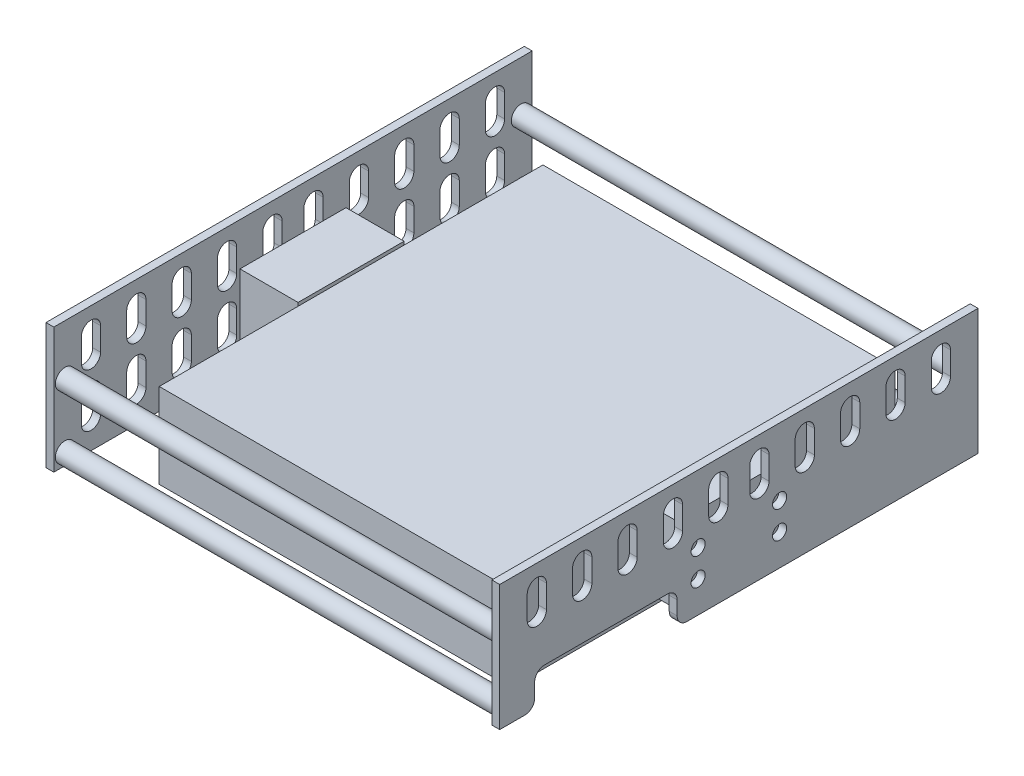
SolidWorks part; units mm, degrees
ref_plane "Front Plane" through (0, 0, 0) normal (0, 0, 1) x (1, 0, 0)
ref_plane "Top Plane" through (0, 0, 0) normal (0, 1, 0) x (1, 0, 0)
ref_plane "Right Plane" through (0, 0, 0) normal (1, 0, 0) x (0, 0, -1)
sketch "Sketch1" plane through (0, 0, 0) normal (1, 0, 0) x (0, 0, -1)
  line L0 (0, 0) -> (0, -16.4338) construction
  line L1 (0, 0) -> (55.8004, 0) construction
  line L2 (0, -16.4338) -> (117.9322, -16.4338) construction
  line L3 (117.9322, -16.4338) -> (117.9322, 0) construction
  line L4 (-2.5019, -18.9357) -> (120.4341, -18.9357) construction
  line L5 (-2.5019, 2.5019) -> (120.4341, 2.5019) construction
  line L6 (-2.5019, 2.5019) -> (-2.5019, -18.9357) construction
  line L7 (120.4341, 2.5019) -> (120.4341, -18.9357) construction
  circle A0 centre (0, 0) radius 2.5019
  circle A1 centre (0, -16.4338) radius 2.5019
  circle A2 centre (117.9322, -16.4338) radius 2.5019
  circle A3 centre (117.9322, 0) radius 2.5019
  dimension "D2" = 5.0038
  dimension "D3" = 21.4376
  dimension "D4" = 122.936
extrude "Boss-Extrude1" add sketch "Sketch1" along normal blind 115.316
ref_plane "Plane1" through (12.7, 0, 0) normal (1, 0, 0) x (0, 0, -1)
sketch "Sketch5" plane through (0, 0, 0) normal (1, 0, 0) x (0, 0, -1)
  line L4 (0, 0) -> (117.9322, -16.4338) construction
  line L5 (58.9661, 12.954) -> (58.9661, -19.558) construction
  line L6 (4.2291, -14.9987) -> (4.2291, 9.7028) construction
  line L8 (6.7183, 1.27) -> (6.7183, 7.2136) construction
  line L10 (4.2291, 9.7028) -> (113.7031, 9.7028) construction
  line L15 (113.7031, -14.9987) -> (4.2291, -14.9987) construction
  line L20 (117.9322, 0) -> (0, -16.4338) construction
  line L29 (64.2747, 1.27) -> (64.2747, 7.2136) construction
  line L38 (66.7639, 1.27) -> (66.7639, 7.2136)
  line L45 (61.7855, 1.27) -> (61.7855, 7.2136)
  line L52 (64.2747, -12.5095) -> (64.2747, -6.5659) construction
  line L61 (66.7639, -12.5095) -> (66.7639, -6.5659)
  line L70 (61.7855, -12.5095) -> (61.7855, -6.5659)
  line L76 (-2.8829, -19.558) -> (120.8151, -19.558)
  line L77 (-2.8829, -19.558) -> (-2.8829, 12.954)
  line L78 (-2.8829, 12.954) -> (120.8151, 12.954)
  line L79 (120.8151, -19.558) -> (120.8151, 12.954)
  line L80 (76.0095, -12.5095) -> (76.0095, -6.5659) construction
  line L81 (78.4987, -12.5095) -> (78.4987, -6.5659)
  line L82 (4.2291, 1.27) -> (4.2291, 7.2136)
  line L83 (9.2075, 1.27) -> (9.2075, 7.2136)
  line L84 (4.2291, 9.7028) -> (9.2075, 9.7028) construction
  line L85 (9.2075, 9.7028) -> (9.2075, -1.2192) construction
  line L86 (9.2075, -1.2192) -> (4.2291, -1.2192) construction
  line L87 (4.2291, -1.2192) -> (4.2291, 9.7028) construction
  line L88 (18.4531, 1.27) -> (18.4531, 7.2136) construction
  line L89 (15.9639, 1.27) -> (15.9639, 7.2136)
  line L90 (20.9423, 1.27) -> (20.9423, 7.2136)
  line L91 (30.1879, 1.27) -> (30.1879, 7.2136) construction
  line L92 (27.6987, 1.27) -> (27.6987, 7.2136)
  line L93 (32.6771, 1.27) -> (32.6771, 7.2136)
  line L94 (41.9227, 1.27) -> (41.9227, 7.2136) construction
  line L95 (39.4335, 1.27) -> (39.4335, 7.2136)
  line L96 (44.4119, 1.27) -> (44.4119, 7.2136)
  line L97 (53.6575, 1.27) -> (53.6575, 7.2136) construction
  line L98 (51.1683, 1.27) -> (51.1683, 7.2136)
  line L99 (56.1467, 1.27) -> (56.1467, 7.2136)
  line L100 (18.4531, -12.5095) -> (18.4531, -6.5659) construction
  line L101 (15.9639, -12.5095) -> (15.9639, -6.5659)
  line L102 (20.9423, -12.5095) -> (20.9423, -6.5659)
  line L103 (30.1879, -12.5095) -> (30.1879, -6.5659) construction
  line L104 (27.6987, -12.5095) -> (27.6987, -6.5659)
  line L105 (32.6771, -12.5095) -> (32.6771, -6.5659)
  line L106 (41.9227, -12.5095) -> (41.9227, -6.5659) construction
  line L107 (39.4335, -12.5095) -> (39.4335, -6.5659)
  line L108 (44.4119, -12.5095) -> (44.4119, -6.5659)
  line L109 (53.6575, -12.5095) -> (53.6575, -6.5659) construction
  line L110 (51.1683, -12.5095) -> (51.1683, -6.5659)
  line L111 (56.1467, -12.5095) -> (56.1467, -6.5659)
  line L112 (6.7183, -12.5095) -> (6.7183, -6.5659) construction
  line L113 (4.2291, -12.5095) -> (4.2291, -6.5659)
  line L114 (9.2075, -12.5095) -> (9.2075, -6.5659)
  line L116 (73.5203, -12.5095) -> (73.5203, -6.5659)
  line L117 (113.7031, 9.7028) -> (113.7031, -14.9987) construction
  line L118 (76.0095, 1.27) -> (76.0095, 7.2136) construction
  line L119 (78.4987, 1.27) -> (78.4987, 7.2136)
  line L120 (73.5203, 1.27) -> (73.5203, 7.2136)
  line L121 (87.7443, 1.27) -> (87.7443, 7.2136) construction
  line L122 (90.2335, 1.27) -> (90.2335, 7.2136)
  line L123 (85.2551, 1.27) -> (85.2551, 7.2136)
  line L124 (87.7443, -12.5095) -> (87.7443, -6.5659) construction
  line L125 (90.2335, -12.5095) -> (90.2335, -6.5659)
  line L126 (85.2551, -12.5095) -> (85.2551, -6.5659)
  line L127 (99.4791, -12.5095) -> (99.4791, -6.5659) construction
  line L128 (101.9683, -12.5095) -> (101.9683, -6.5659)
  line L129 (96.9899, -12.5095) -> (96.9899, -6.5659)
  line L130 (99.4791, 1.27) -> (99.4791, 7.2136) construction
  line L131 (101.9683, 1.27) -> (101.9683, 7.2136)
  line L132 (96.9899, 1.27) -> (96.9899, 7.2136)
  line L133 (111.2139, 1.27) -> (111.2139, 7.2136) construction
  line L134 (113.7031, 1.27) -> (113.7031, 7.2136)
  line L135 (108.7247, 1.27) -> (108.7247, 7.2136)
  line L136 (111.2139, -12.5095) -> (111.2139, -6.5659) construction
  line L137 (113.7031, -12.5095) -> (113.7031, -6.5659)
  line L138 (108.7247, -12.5095) -> (108.7247, -6.5659)
  line L140 (-6.1459, 2.5019) -> (0, 2.5019) construction
  line L146 (46.609, -13.3223) -> (71.3232, -13.3223) construction
  line L147 (46.609, -13.3223) -> (46.609, -2.6162) construction
  line L148 (46.609, -2.6162) -> (71.3232, -2.6162) construction
  line L149 (71.3232, -13.3223) -> (71.3232, -2.6162) construction
  line L150 (46.609, -13.3223) -> (71.3232, -2.6162) construction
  line L151 (46.609, -2.6162) -> (71.3232, -13.3223) construction
  arc A40 (4.2291, 1.27) -> (9.2075, 1.27) centre (6.7183, 1.27) ccw
  arc A41 (9.2075, 7.2136) -> (4.2291, 7.2136) centre (6.7183, 7.2136) ccw
  arc A42 (15.9639, 1.27) -> (20.9423, 1.27) centre (18.4531, 1.27) ccw
  arc A43 (20.9423, 7.2136) -> (15.9639, 7.2136) centre (18.4531, 7.2136) ccw
  arc A44 (27.6987, 1.27) -> (32.6771, 1.27) centre (30.1879, 1.27) ccw
  arc A45 (32.6771, 7.2136) -> (27.6987, 7.2136) centre (30.1879, 7.2136) ccw
  arc A46 (39.4335, 1.27) -> (44.4119, 1.27) centre (41.9227, 1.27) ccw
  arc A47 (44.4119, 7.2136) -> (39.4335, 7.2136) centre (41.9227, 7.2136) ccw
  arc A48 (51.1683, 1.27) -> (56.1467, 1.27) centre (53.6575, 1.27) ccw
  arc A49 (56.1467, 7.2136) -> (51.1683, 7.2136) centre (53.6575, 7.2136) ccw
  arc A50 (15.9639, -12.5095) -> (20.9423, -12.5095) centre (18.4531, -12.5095) ccw
  arc A51 (20.9423, -6.5659) -> (15.9639, -6.5659) centre (18.4531, -6.5659) ccw
  arc A52 (27.6987, -12.5095) -> (32.6771, -12.5095) centre (30.1879, -12.5095) ccw
  arc A53 (32.6771, -6.5659) -> (27.6987, -6.5659) centre (30.1879, -6.5659) ccw
  arc A54 (39.4335, -12.5095) -> (44.4119, -12.5095) centre (41.9227, -12.5095) ccw
  arc A55 (44.4119, -6.5659) -> (39.4335, -6.5659) centre (41.9227, -6.5659) ccw
  arc A56 (51.1683, -12.5095) -> (56.1467, -12.5095) centre (53.6575, -12.5095) ccw
  arc A57 (56.1467, -6.5659) -> (51.1683, -6.5659) centre (53.6575, -6.5659) ccw
  arc A58 (4.2291, -12.5095) -> (9.2075, -12.5095) centre (6.7183, -12.5095) ccw
  arc A59 (9.2075, -6.5659) -> (4.2291, -6.5659) centre (6.7183, -6.5659) ccw
  circle A60 centre (0, 0) radius 2.5019 construction
  circle A61 centre (0, -16.4338) radius 2.5019 construction
  circle A62 centre (117.9322, 0) radius 2.5019 construction
  circle A63 centre (117.9322, -16.4338) radius 2.5019 construction
  arc A64 (66.7639, 1.27) -> (61.7855, 1.27) centre (64.2747, 1.27) cw
  arc A65 (61.7855, 7.2136) -> (66.7639, 7.2136) centre (64.2747, 7.2136) cw
  arc A66 (66.7639, -12.5095) -> (61.7855, -12.5095) centre (64.2747, -12.5095) cw
  arc A67 (61.7855, -6.5659) -> (66.7639, -6.5659) centre (64.2747, -6.5659) cw
  arc A68 (78.4987, -12.5095) -> (73.5203, -12.5095) centre (76.0095, -12.5095) cw
  arc A69 (73.5203, -6.5659) -> (78.4987, -6.5659) centre (76.0095, -6.5659) cw
  arc A70 (78.4987, 1.27) -> (73.5203, 1.27) centre (76.0095, 1.27) cw
  arc A71 (73.5203, 7.2136) -> (78.4987, 7.2136) centre (76.0095, 7.2136) cw
  arc A72 (90.2335, 1.27) -> (85.2551, 1.27) centre (87.7443, 1.27) cw
  arc A73 (85.2551, 7.2136) -> (90.2335, 7.2136) centre (87.7443, 7.2136) cw
  arc A74 (90.2335, -12.5095) -> (85.2551, -12.5095) centre (87.7443, -12.5095) cw
  arc A75 (85.2551, -6.5659) -> (90.2335, -6.5659) centre (87.7443, -6.5659) cw
  arc A76 (101.9683, -12.5095) -> (96.9899, -12.5095) centre (99.4791, -12.5095) cw
  arc A77 (96.9899, -6.5659) -> (101.9683, -6.5659) centre (99.4791, -6.5659) cw
  arc A78 (101.9683, 1.27) -> (96.9899, 1.27) centre (99.4791, 1.27) cw
  arc A79 (96.9899, 7.2136) -> (101.9683, 7.2136) centre (99.4791, 7.2136) cw
  arc A80 (113.7031, 1.27) -> (108.7247, 1.27) centre (111.2139, 1.27) cw
  arc A81 (108.7247, 7.2136) -> (113.7031, 7.2136) centre (111.2139, 7.2136) cw
  arc A82 (113.7031, -12.5095) -> (108.7247, -12.5095) centre (111.2139, -12.5095) cw
  arc A83 (108.7247, -6.5659) -> (113.7031, -6.5659) centre (111.2139, -6.5659) cw
  circle A84 centre (48.4314, -4.4386) radius 1.8225
  circle A85 centre (48.4314, -11.4998) radius 1.8225
  circle A86 centre (69.5007, -4.4386) radius 1.8224
  circle A87 centre (69.5007, -11.4998) radius 1.8224
  point P15 (58.9661, -8.2169)
  point P19 (64.2747, 4.2418)
  point P26 (64.2747, -9.5377)
  point P36 (76.0095, -9.5377)
  point P43 (76.0095, 4.2418)
  point P50 (87.7443, 4.2418)
  point P57 (87.7443, -9.5377)
  point P64 (99.4791, -9.5377)
  point P71 (99.4791, 4.2418)
  point P78 (111.2139, 4.2418)
  point P88 (111.2139, -9.5377)
  point P100 (58.9661, -7.9692)
  point P166 (6.7183, 4.2418)
  point P180 (18.4531, 4.2418)
  point P187 (30.1879, 4.2418)
  point P194 (41.9227, 4.2418)
  point P201 (53.6575, 4.2418)
  point P208 (18.4531, -9.5377)
  point P215 (30.1879, -9.5377)
  point P222 (41.9227, -9.5377)
  point P229 (53.6575, -9.5377)
  point P236 (6.7183, -9.5377)
  dimension "D3" = 123.698
  dimension "D8" = 3.6449
  dimension "D4" = 10.4521
  dimension "D5" = 24.7142
  dimension "D6" = 10.7061
  dimension "D11" = 32.512
  dimension "D13" = 3.2512
  dimension "D14" = 7.112
  dimension "D15" = 4.9784
  dimension "D16" = 10.922
  dimension "D19" = 13.7795
  dimension "D20" = 11.7348
  dimension "D7" = 6.2357
  dimension "D17" = 5
  dimension "D18" = 2
extrude "Boss-Extrude3" add sketch "Sketch5" along normal blind 2.032
ref_plane "Plane2" through (115.316, 0, 0) normal (1, 0, 0) x (0, 0, -1)
sketch "Sketch6" plane through (115.316, 0, 0) normal (1, 0, 0) x (0, 0, -1)
  line L0 (120.8151, 12.954) -> (-2.8829, 12.954) construction
  line L1 (-2.8829, -19.558) -> (3.6195, -19.558)
  line L2 (-2.8829, -19.558) -> (-2.8829, 12.954)
  line L3 (-2.8829, 12.954) -> (120.8151, 12.954)
  line L4 (120.8151, -19.558) -> (120.8151, 12.954)
  line L5 (-2.8829, -19.558) -> (120.8151, 12.954) construction
  line L6 (-2.8829, 12.954) -> (120.8151, -19.558) construction
  line L7 (-2.8829, 12.954) -> (-2.8829, -19.558) construction
  line L8 (6.1595, -17.018) -> (6.1595, -13.4112)
  line L9 (8.6995, -10.8712) -> (40.4495, -10.8712)
  line L10 (42.9895, -13.4112) -> (42.9895, -17.018)
  line L11 (45.5295, -19.558) -> (120.8151, -19.558)
  line L88 (15.9639, 7.2136) -> (15.9639, 1.27)
  line L89 (20.9423, 1.27) -> (20.9423, 7.2136)
  line L90 (9.2075, 1.27) -> (9.2075, 7.2136)
  line L91 (4.2291, 7.2136) -> (4.2291, 1.27)
  line L92 (9.2075, 1.27) -> (9.2075, 7.2136)
  line L93 (4.2291, 7.2136) -> (4.2291, 1.27)
  line L94 (27.6987, 7.2136) -> (27.6987, 1.27)
  line L95 (32.6771, 1.27) -> (32.6771, 7.2136)
  line L96 (39.4335, 7.2136) -> (39.4335, 1.27)
  line L97 (44.4119, 1.27) -> (44.4119, 7.2136)
  line L98 (51.1683, 7.2136) -> (51.1683, 1.27)
  line L99 (56.1467, 1.27) -> (56.1467, 7.2136)
  line L100 (15.9639, 7.2136) -> (15.9639, 1.27) construction
  line L101 (58.9661, 12.954) -> (58.9661, -19.558) construction
  line L102 (61.7855, 1.27) -> (61.7855, 7.2136)
  line L103 (66.7639, 7.2136) -> (66.7639, 1.27)
  line L104 (73.5203, 1.27) -> (73.5203, 7.2136)
  line L105 (78.4987, 7.2136) -> (78.4987, 1.27)
  line L106 (85.2551, 1.27) -> (85.2551, 7.2136)
  line L107 (90.2335, 7.2136) -> (90.2335, 1.27)
  line L108 (96.9899, 1.27) -> (96.9899, 7.2136)
  line L109 (101.9683, 7.2136) -> (101.9683, 1.27)
  line L110 (113.7031, 7.2136) -> (113.7031, 1.27)
  line L111 (108.7247, 1.27) -> (108.7247, 7.2136)
  circle A5 centre (48.4314, -4.4386) radius 1.8225
  circle A6 centre (48.4314, -4.4386) radius 1.8225 construction
  circle A7 centre (69.5007, -4.4386) radius 1.8224
  circle A8 centre (69.5007, -11.4998) radius 1.8224
  circle A9 centre (48.4314, -11.4998) radius 1.8225
  circle A10 centre (48.4314, -11.4998) radius 1.8225 construction
  circle A11 centre (69.5007, -11.4998) radius 1.8225 construction
  circle A12 centre (69.5007, -4.4386) radius 1.8225 construction
  arc A70 (20.9423, 7.2136) -> (15.9639, 7.2136) centre (18.4531, 7.2136) ccw
  arc A71 (15.9639, 1.27) -> (20.9423, 1.27) centre (18.4531, 1.27) ccw
  arc A72 (4.2291, 1.27) -> (9.2075, 1.27) centre (6.7183, 1.27) ccw
  arc A73 (9.2075, 7.2136) -> (4.2291, 7.2136) centre (6.7183, 7.2136) ccw
  arc A74 (4.2291, 1.27) -> (9.2075, 1.27) centre (6.7183, 1.27) ccw
  arc A75 (9.2075, 7.2136) -> (4.2291, 7.2136) centre (6.7183, 7.2136) ccw
  arc A76 (32.6771, 7.2136) -> (27.6987, 7.2136) centre (30.1879, 7.2136) ccw
  arc A77 (27.6987, 1.27) -> (32.6771, 1.27) centre (30.1879, 1.27) ccw
  arc A78 (44.4119, 7.2136) -> (39.4335, 7.2136) centre (41.9227, 7.2136) ccw
  arc A79 (39.4335, 1.27) -> (44.4119, 1.27) centre (41.9227, 1.27) ccw
  arc A80 (56.1467, 7.2136) -> (51.1683, 7.2136) centre (53.6575, 7.2136) ccw
  arc A81 (51.1683, 1.27) -> (56.1467, 1.27) centre (53.6575, 1.27) ccw
  arc A82 (61.7855, 7.2136) -> (66.7639, 7.2136) centre (64.2747, 7.2136) cw
  arc A83 (66.7639, 1.27) -> (61.7855, 1.27) centre (64.2747, 1.27) cw
  arc A84 (73.5203, 7.2136) -> (78.4987, 7.2136) centre (76.0095, 7.2136) cw
  arc A85 (78.4987, 1.27) -> (73.5203, 1.27) centre (76.0095, 1.27) cw
  arc A86 (85.2551, 7.2136) -> (90.2335, 7.2136) centre (87.7443, 7.2136) cw
  arc A87 (90.2335, 1.27) -> (85.2551, 1.27) centre (87.7443, 1.27) cw
  arc A88 (96.9899, 7.2136) -> (101.9683, 7.2136) centre (99.4791, 7.2136) cw
  arc A89 (101.9683, 1.27) -> (96.9899, 1.27) centre (99.4791, 1.27) cw
  arc A90 (108.7247, 7.2136) -> (113.7031, 7.2136) centre (111.2139, 7.2136) cw
  arc A91 (113.7031, 1.27) -> (108.7247, 1.27) centre (111.2139, 1.27) cw
  arc A92 (42.9895, -17.018) -> (45.5295, -19.558) centre (45.5295, -17.018) ccw
  arc A93 (40.4495, -10.8712) -> (42.9895, -13.4112) centre (40.4495, -13.4112) cw
  arc A94 (6.1595, -13.4112) -> (8.6995, -10.8712) centre (8.6995, -13.4112) cw
  arc A95 (6.1595, -17.018) -> (3.6195, -19.558) centre (3.6195, -17.018) cw
  point P0 (58.9661, -3.302)
  point P79 (42.9895, -19.558)
  point P82 (42.9895, -10.8712)
  point P85 (6.1595, -10.8712)
  point P88 (6.1595, -19.558)
  dimension "D6" = 2.54
  dimension "D3" = 8.6868
  dimension "D4" = 36.83
  dimension "D5" = 9.0424
  dimension "D1" = 0
  dimension "D2" = 5
extrude "Boss-Extrude4" add sketch "Sketch6" along normal blind 2.032 separate body
sketch "Sketch7" plane through (115.316, 0, 0) normal (-1, 0, 0) x (0, 0, 1)
  line L0 (-69.5007, -4.4386) -> (-48.4314, -11.4998) construction
  line L1 (-72.6758, -17.8498) -> (-45.2564, -17.8498)
  line L2 (-72.6758, -17.8498) -> (-72.6758, 1.9114)
  line L3 (-72.6758, 1.9114) -> (-45.2564, 1.9114)
  line L4 (-45.2564, -17.8498) -> (-45.2564, 1.9114)
  line L5 (-72.6758, -17.8498) -> (-45.2564, 1.9114) construction
  line L6 (-72.6758, 1.9114) -> (-45.2564, -17.8498) construction
  line L7 (-69.5007, -4.4386) -> (-69.5007, 1.9114) construction
  line L8 (-69.5007, -4.4386) -> (-72.6758, -4.4386) construction
  point P0 (-58.9661, -7.9692)
  point P9 (-58.9661, -7.9692)
  dimension "D1" = 6.35
  dimension "D2" = 3.175
extrude "Boss-Extrude5" add sketch "Sketch7" along normal blind 7.239
sketch "Sketch8" plane through (2.032, 0, 0) normal (1, 0, 0) x (0, 0, -1)
  line L0 (48.4314, -4.4386) -> (69.5007, -11.4998) construction
  line L1 (45.2564, -17.8498) -> (72.6757, -17.8498)
  line L2 (45.2564, -17.8498) -> (45.2564, 1.9114)
  line L3 (45.2564, 1.9114) -> (72.6757, 1.9114)
  line L4 (72.6757, -17.8498) -> (72.6757, 1.9114)
  line L5 (45.2564, -17.8498) -> (72.6757, 1.9114) construction
  line L6 (45.2564, 1.9114) -> (72.6757, -17.8498) construction
  line L7 (48.4314, -4.4386) -> (48.4314, 1.9114) construction
  line L8 (48.4314, -4.4386) -> (45.2564, -4.4386) construction
  point P0 (58.9661, -7.9692)
  dimension "D1" = 6.35
  dimension "D2" = 3.175
extrude "Boss-Extrude6" add sketch "Sketch8" along normal blind 15.0241
ref_plane "Plane3" through (0, -20.8915, 0) normal (0, -1, 0) x (-1, 0, 0)
sketch "Sketch9" plane through (0, -20.8915, 0) normal (0, -1, 0) x (-1, 0, 0)
  line L0 (-17.0561, 72.6757) -> (-17.0561, 45.2564) construction
  line L1 (-17.0561, 9.3472) -> (-108.077, 9.3472)
  line L2 (-17.0561, 9.3472) -> (-17.0561, 108.585)
  line L3 (-17.0561, 108.585) -> (-108.077, 108.585)
  line L4 (-108.077, 9.3472) -> (-108.077, 108.585)
  line L5 (-17.0561, 9.3472) -> (-108.077, 108.585) construction
  line L6 (-17.0561, 108.585) -> (-108.077, 9.3472) construction
  line L7 (-108.077, 45.2564) -> (-108.077, 72.6758) construction
  line L8 (-115.316, 115.4303) -> (-2.032, 115.4303) construction
  line L9 (-17.0561, 108.585) -> (-17.0561, 115.4303) construction
  line L10 (-17.0561, 9.3472) -> (-17.0561, 2.5019) construction
  line L11 (-2.032, 2.5019) -> (-115.316, 2.5019) construction
  point P0 (-62.5665, 58.9661)
  dimension "D1" = 6.8453
extrude "Boss-Extrude7" add sketch "Sketch9" against normal blind 21.9329 separate body contours L1 L4 L3 L2
sketch "Sketch10" plane through (17.0561, 0, 0) normal (-1, 0, 0) x (0, 0, 1)
  line L0 (-108.585, 1.0414) -> (-9.3472, -20.8915) construction
  circle A0 centre (-58.9661, -9.9251) radius 0.508
  dimension "D1" = 1.016
extrude "Cut-Extrude1" cut sketch "Sketch10" against normal blind 2.54 and the other way blind 2.54
sketch "Sketch11" plane through (108.077, 0, 0) normal (1, 0, 0) x (0, 0, -1)
  line L0 (9.3472, 1.0414) -> (108.585, -20.8915) construction
  circle A0 centre (58.9661, -9.9251) radius 0.508
  dimension "D1" = 1.016
extrude "Cut-Extrude2" cut sketch "Sketch11" against normal blind 2.54 and the other way blind 2.54
equation "\"x\"= 5cm"
